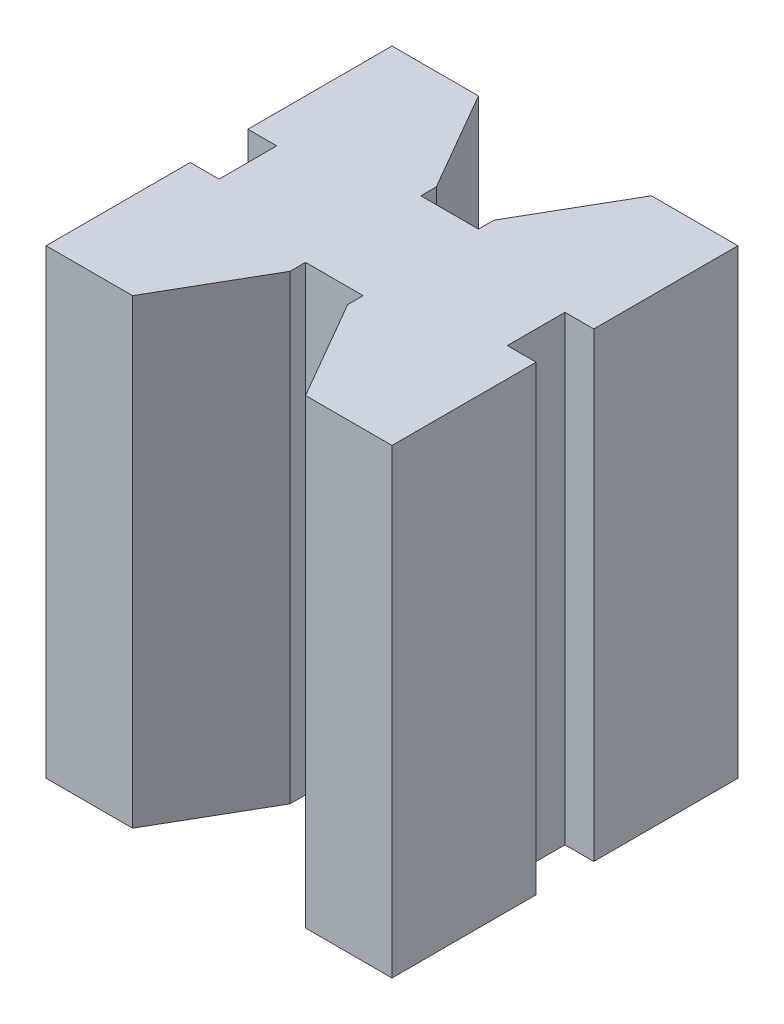
SolidWorks part; units mm, degrees
ref_plane "Front Plane" through (0, 0, 0) normal (0, 0, 1) x (1, 0, 0)
ref_plane "Top Plane" through (0, 0, 0) normal (0, 1, 0) x (1, 0, 0)
ref_plane "Right Plane" through (0, 0, 0) normal (1, 0, 0) x (0, 0, -1)
sketch "Sketch1" plane through (0, 0, 0) normal (0, 1, 0) x (1, 0, 0)
  line L68 (-30, -15) -> (0, -15) construction
  line L69 (-30, -12.5) -> (-27.5, -12.5)
  line L70 (-15, 0) -> (-15, -30) construction
  line L71 (-27.5, -12.5) -> (-27.5, -17.5)
  line L72 (-27.5, -17.5) -> (-30, -17.5)
  line L73 (0, -12.5) -> (-2.5, -12.5)
  line L74 (-2.5, -12.5) -> (-2.5, -17.5)
  line L75 (-2.5, -17.5) -> (0, -17.5)
  line L76 (-17.5, -20) -> (-17.5, -21.3397)
  line L77 (-7.5, -30) -> (-12.5, -21.3397)
  line L78 (-17.5, -20) -> (-12.5, -20)
  line L79 (-12.5, -20) -> (-12.5, -21.3397)
  line L80 (-17.5, -10) -> (-17.5, -8.6603)
  line L81 (-30, 0) -> (-30, -12.5)
  line L82 (-17.5, -10) -> (-12.5, -10)
  line L83 (-30, -17.5) -> (-30, -30)
  line L86 (-12.5, -10) -> (-12.5, -8.6603)
  line L88 (-30, 0) -> (-22.5, 0)
  line L89 (-7.5, 0) -> (0, 0)
  line L90 (-30, -30) -> (-22.5, -30)
  line L91 (-7.5, -30) -> (0, -30)
  line L92 (-17.5, -21.3397) -> (-22.5, -30)
  line L93 (-12.5, -8.6603) -> (-7.5, 0)
  line L94 (-22.5, 0) -> (-17.5, -8.6603)
  line L95 (0, -12.5) -> (0, 0)
  line L96 (0, -17.5) -> (0, -30)
  point P22 (-15, -20)
  point P26 (-15, -32.2661)
  point P32 (-14.7773, -23.9561)
  dimension "D1" = 30
  dimension "D2" = 5
  dimension "D3" = 10
  dimension "D4" = 5
  dimension "D5" = 15
  dimension "D6" = 25
  dimension "D7" = 30
  dimension "D8" = 60
  dimension "D9" = 60
  dimension "D10" = 60
  dimension "D11" = 60
  dimension "D12" = 1.3397
  dimension "D13" = 15
  dimension "D14" = 5
  dimension "D15" = 2.5
  dimension "D16" = 12.5
  dimension "D17" = 2.5
  dimension "D18" = 7.5
  dimension "D19" = 12.5
extrude "Boss-Extrude2" add sketch "Sketch1" along normal blind 40
